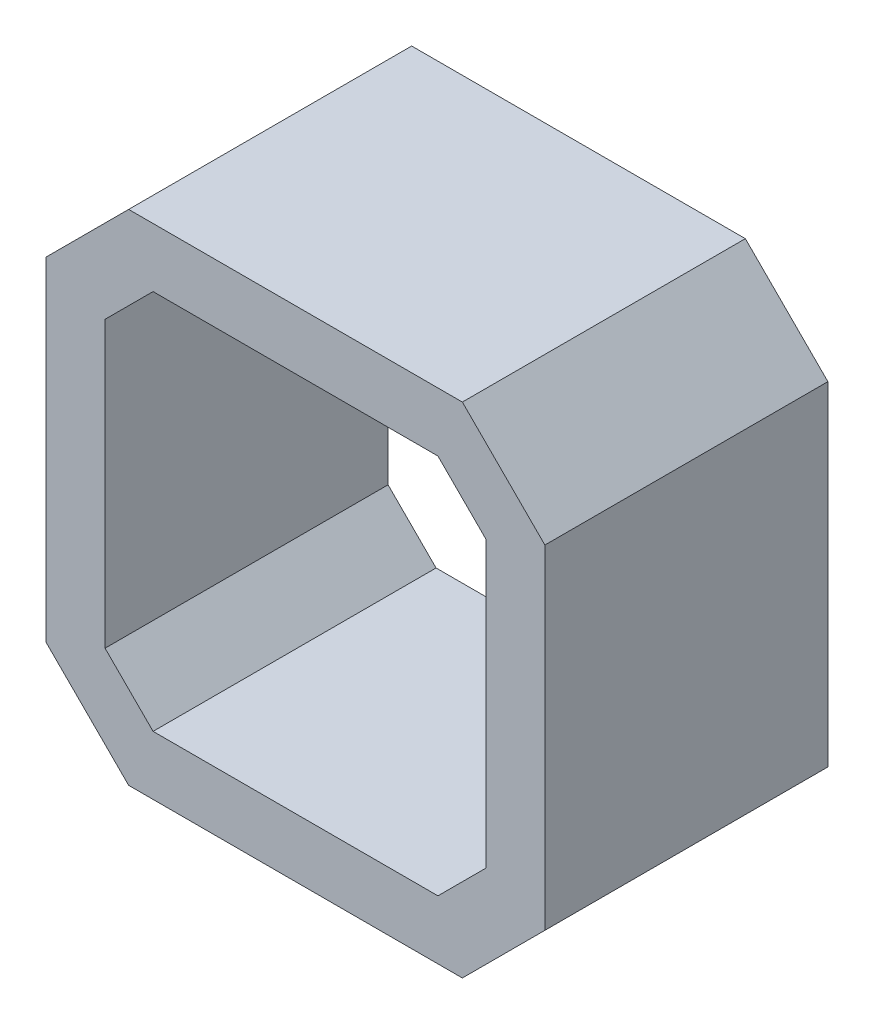
SolidWorks part; units mm, degrees
ref_plane "Front Plane" through (0, 0, 0) normal (0, 0, 1) x (1, 0, 0)
ref_plane "Top Plane" through (0, 0, 0) normal (0, 1, 0) x (1, 0, 0)
ref_plane "Right Plane" through (0, 0, 0) normal (1, 0, 0) x (0, 0, -1)
sketch "Sketch1" plane through (0, 0, 0) normal (0, 0, 1) x (1, 0, 0)
  line L0 (-14.15, 21.15) -> (-21.15, 14.15)
  line L1 (14.15, -21.15) -> (-14.15, -21.15)
  line L2 (21.15, -14.15) -> (21.15, 14.15)
  line L3 (14.15, 21.15) -> (-14.15, 21.15)
  line L4 (-21.15, -14.15) -> (-21.15, 14.15)
  line L5 (21.15, -21.15) -> (-21.15, 21.15) construction
  line L6 (21.15, 21.15) -> (-21.15, -21.15) construction
  line L7 (-14.15, -21.15) -> (-21.15, -14.15)
  line L8 (21.15, -14.15) -> (14.15, -21.15)
  line L9 (21.15, 14.15) -> (14.15, 21.15)
  line L10 (-12.0789, 16.15) -> (-16.15, 12.0789)
  line L11 (-16.15, -12.0789) -> (-16.15, 12.0789)
  line L12 (-12.0789, -16.15) -> (-16.15, -12.0789)
  line L13 (12.0789, -16.15) -> (-12.0789, -16.15)
  line L14 (16.15, -12.0789) -> (12.0789, -16.15)
  line L15 (16.15, -12.0789) -> (16.15, 12.0789)
  line L16 (16.15, 12.0789) -> (12.0789, 16.15)
  line L17 (12.0789, 16.15) -> (-12.0789, 16.15)
  point P0 (0, 0)
  dimension "D1" = 42.3
  dimension "D2" = 42.3
  dimension "D3" = 5
extrude "Boss-Extrude1" add sketch "Sketch1" along normal blind 24
